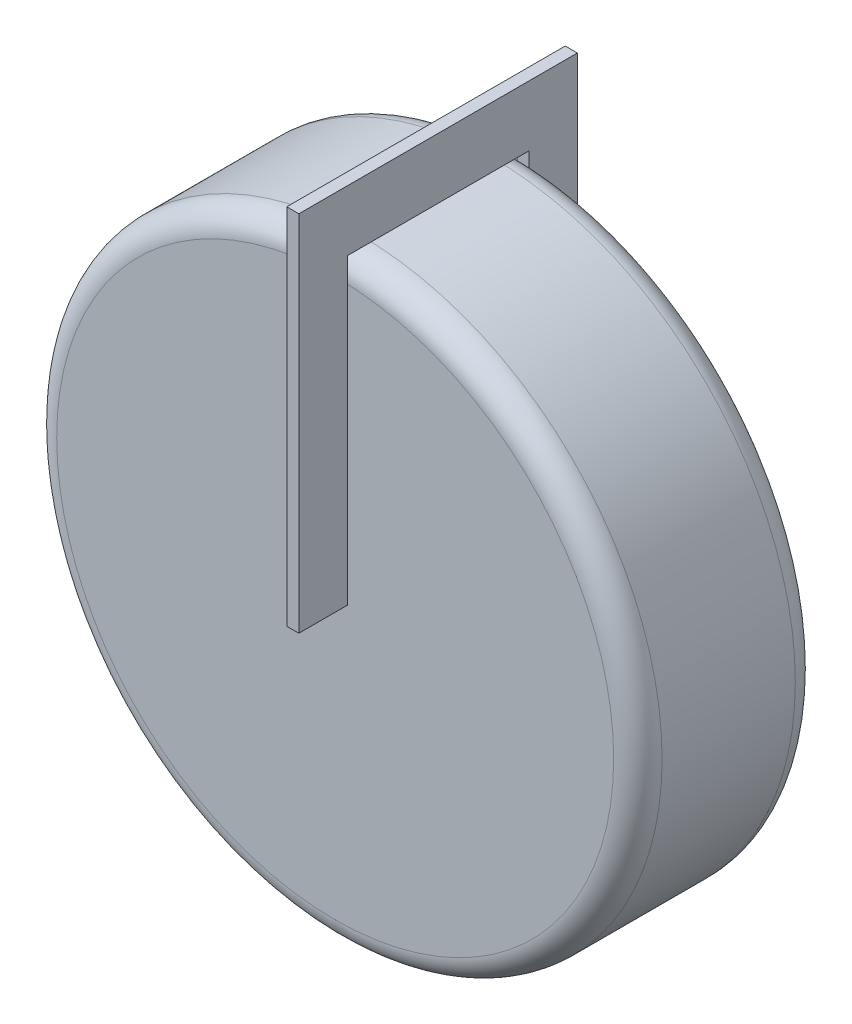
SolidWorks part; units mm, degrees
ref_plane "Front Plane" through (0, 0, 0) normal (0, 0, 1) x (1, 0, 0)
ref_plane "Top Plane" through (0, 0, 0) normal (0, 1, 0) x (1, 0, 0)
ref_plane "Right Plane" through (0, 0, 0) normal (1, 0, 0) x (0, 0, -1)
sketch "Sketch1" plane through (0, 0, 0) normal (0, 0, 1) x (1, 0, 0)
  line L0 (0, 0) -> (0, 25)
  circle A0 centre (0, 0) radius 25
  dimension "D1" = 50
extrude "Boss-Extrude1" add sketch "Sketch1" along normal blind 15 contours A0
sketch "Sketch2" plane through (0, 0, 0) normal (1, 0, 0) x (0, 0, -1)
  line L13 (0, 0) -> (4, 0)
  line L14 (0, 0) -> (0, 30)
  line L15 (0, 30) -> (4, 30)
  line L16 (4, 0) -> (4, 30)
  line L17 (0, 30) -> (-15, 30)
  line L18 (0, 30) -> (0, 25)
  line L19 (0, 25) -> (-15, 25)
  line L20 (-15, 30) -> (-15, 25)
  line L21 (-15, 30) -> (-19, 30)
  line L22 (-15, 30) -> (-15, 0)
  line L23 (-15, 0) -> (-19, 0)
  line L24 (-19, 30) -> (-19, 0)
  dimension "D1" = 30
  dimension "D2" = 30
  dimension "D3" = 4
  dimension "D4" = 4
extrude "Boss-Extrude3" add sketch "Sketch2" along normal blind 1 separate body contours L21 L24 L23 L22 L20 | L17 L20 L19 L14 | L13 L16 L15 L14
fillet "Fillet1" radius 2 2 edges at (25, 0, 15) (25, 0, 0)
